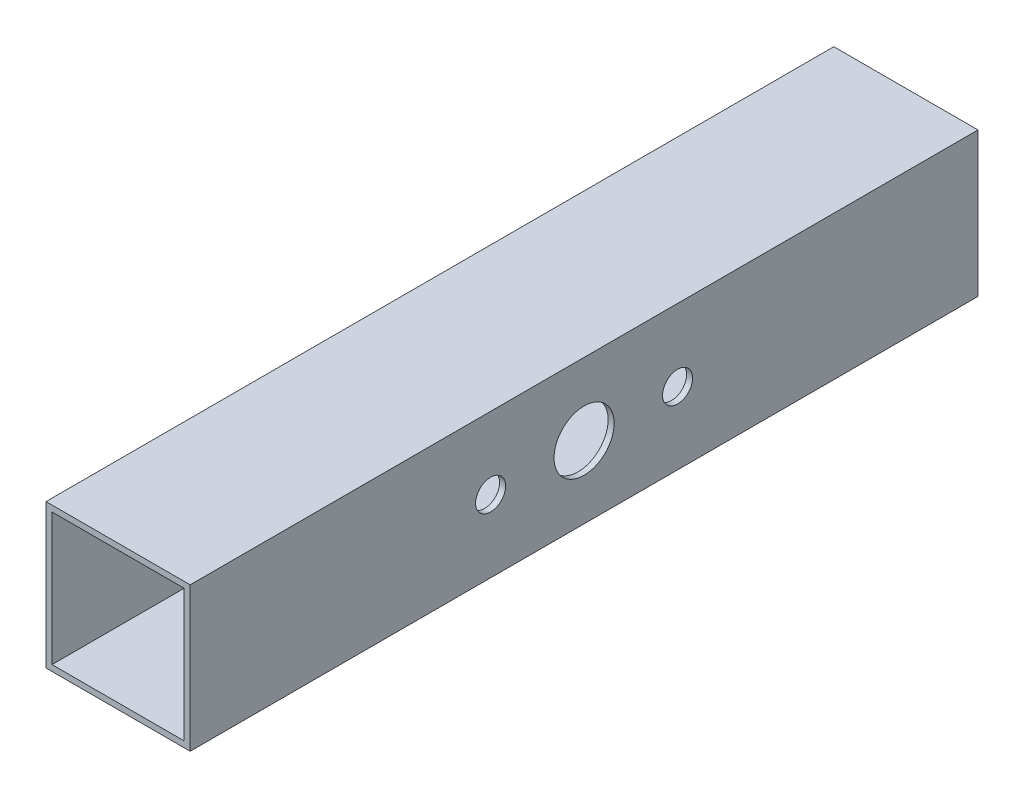
SolidWorks part; units mm, degrees
ref_plane "Front Plane" through (0, 0, 0) normal (0, 0, 1) x (1, 0, 0)
ref_plane "Top Plane" through (0, 0, 0) normal (0, 1, 0) x (1, 0, 0)
ref_plane "Right Plane" through (0, 0, 0) normal (1, 0, 0) x (0, 0, -1)
sketch "Sketch2" plane through (0, 0, 0) normal (0, 0, 1) x (1, 0, 0)
  line L0 (-34.925, 34.925) -> (34.925, 34.925)
  line L1 (-38.1, -38.1) -> (38.1, -38.1)
  line L2 (-38.1, -38.1) -> (-38.1, 38.1)
  line L3 (-38.1, 38.1) -> (38.1, 38.1)
  line L4 (38.1, -38.1) -> (38.1, 38.1)
  line L5 (-38.1, -38.1) -> (38.1, 38.1) construction
  line L6 (-38.1, 38.1) -> (38.1, -38.1) construction
  line L7 (34.925, -34.925) -> (34.925, 34.925)
  line L8 (-34.925, -34.925) -> (34.925, -34.925)
  line L9 (-34.925, -34.925) -> (-34.925, 34.925)
  point P0 (0, 0)
  dimension "D1" = 76.2
  dimension "D2" = 3.175
extrude "Boss-Extrude1" add sketch "Sketch2" along normal mid plane 416.4
sketch "Sketch3" plane through (-38.1, 0, 0) normal (-1, 0, 0) x (0, 0, 1)
  line L0 (49.4109, 0) -> (-49.4109, 0) construction
  circle A0 centre (0, 0) radius 15.875
  circle A1 centre (-49.4109, 0) radius 7.9375
  circle A2 centre (49.4109, 0) radius 7.9375
  point P5 (0, 0)
  dimension "D1" = 31.75
  dimension "D3" = 15.875
  dimension "D4" = 15.875
  dimension "D2" = 98.8219
extrude "Cut-Extrude1" cut sketch "Sketch3" against normal through all
